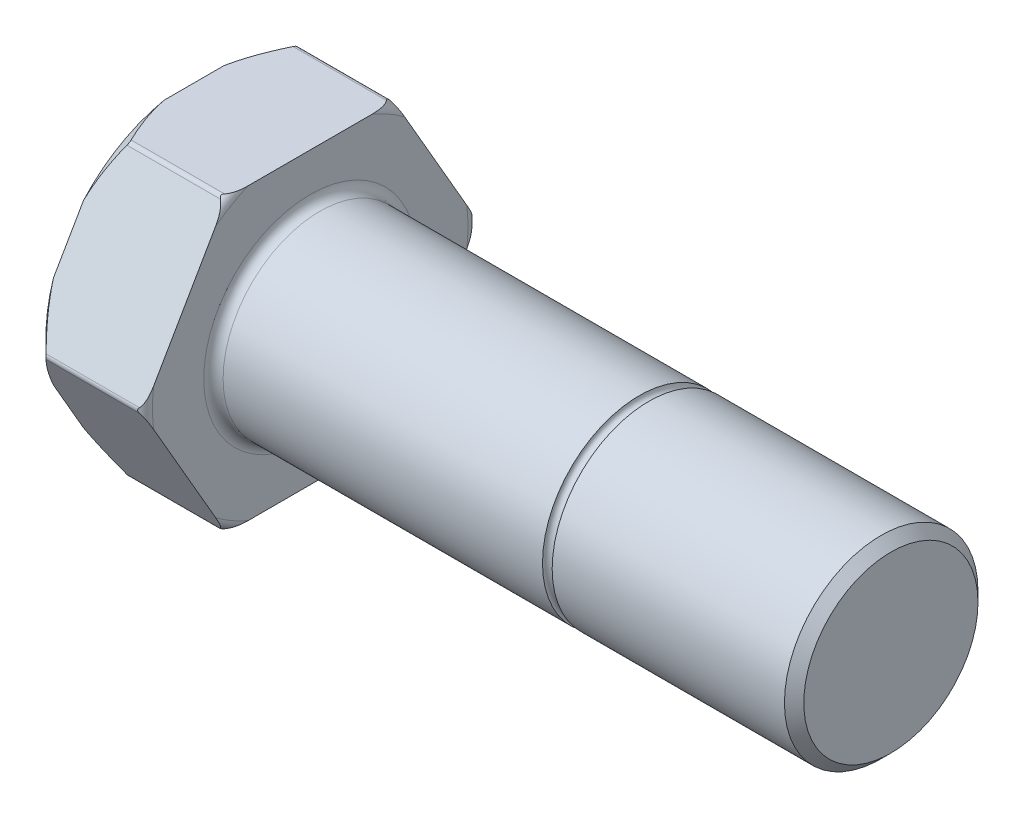
SolidWorks part; units mm, degrees
ref_plane "Alzado" through (0, 0, 0) normal (0, 0, 1) x (1, 0, 0)
ref_plane "Planta" through (0, 0, 0) normal (0, 1, 0) x (1, 0, 0)
ref_plane "Vista lateral" through (0, 0, 0) normal (1, 0, 0) x (0, 0, -1)
sketch "Croquis1" plane through (0, 0, 0) normal (0, 0, 1) x (1, 0, 0)
  line L0 (0, 0) -> (0, 17.3)
  line L1 (0, 17.3) -> (12, 17.3)
  line L2 (12, 17.3) -> (12, 10)
  line L3 (12, 10) -> (46, 10)
  line L4 (72, 10) -> (72, 0)
  line L5 (72, 0) -> (0, 0)
  line L6 (47, 10) -> (72, 10)
  arc A0 (46, 10) -> (47, 10) centre (46.5, 10) ccw
  dimension "D5" = 0.5
  dimension "D1" = 10
  dimension "D2" = 17.3
  dimension "D3" = 12
  dimension "D4" = 60
  dimension "D6" = 1
  dimension "D7" = 25
revolve "Revolución1" add sketch "Croquis1" angle 360 about L5
fillet "Redondeo1" radius 1 2 edges at (12, 0, -17.3) (12, 0, -10)
chamfer "Chaflán1" distance 1 angle 45 1 edges at (72, 0, -10)
sketch "Croquis4" plane through (0, 0, 0) normal (0, 0, 1) x (1, 0, 0)
  line L0 (0, 0) -> (71, 0) construction
  line L2 (0, 17.3) -> (0, 15.3)
  line L3 (0, 17.3) -> (0, -17.3) construction
  line L4 (0, 15.3) -> (2, 17.3)
  line L5 (11, 17.3) -> (0, 17.3) construction
  line L6 (2, 17.3) -> (0, 17.3)
  line L7 (71, -10) -> (71, 10) construction
  dimension "D1" = 2
  dimension "D2" = 2
revolve "Cortar-Revolución1" cut sketch "Croquis4" angle 360 about L0
sketch "Croquis2" plane through (0, 0, 0) normal (-1, 0, 0) x (0, 0, 1)
  line L1 (8.65, 14.9822) -> (-8.65, 14.9822)
  line L2 (-8.65, 14.9822) -> (-17.3, 0)
  line L3 (-17.3, 0) -> (-8.65, -14.9822)
  line L4 (-8.65, -14.9822) -> (8.65, -14.9822)
  line L5 (8.65, -14.9822) -> (17.3, 0)
  line L6 (17.3, 0) -> (8.65, 14.9822)
  circle A0 centre (0, 0) radius 14.9822 construction
  circle A1 centre (0, 0) radius 18.1223
  dimension "D2" = 36.2446
  dimension "D1" = 29.9645
extrude "Cortar-Extruir1" cut sketch "Croquis2" against normal up to next
fillet "Redondeo3" radius 0.5 6 edges at (6.5, 14.9822, 8.65) (6.5, 0, 17.3) (6.5, -14.9822, 8.65) (6.5, 14.9822, -8.65) (6.5, 0, -17.3) (6.5, -14.9822, -8.65)
